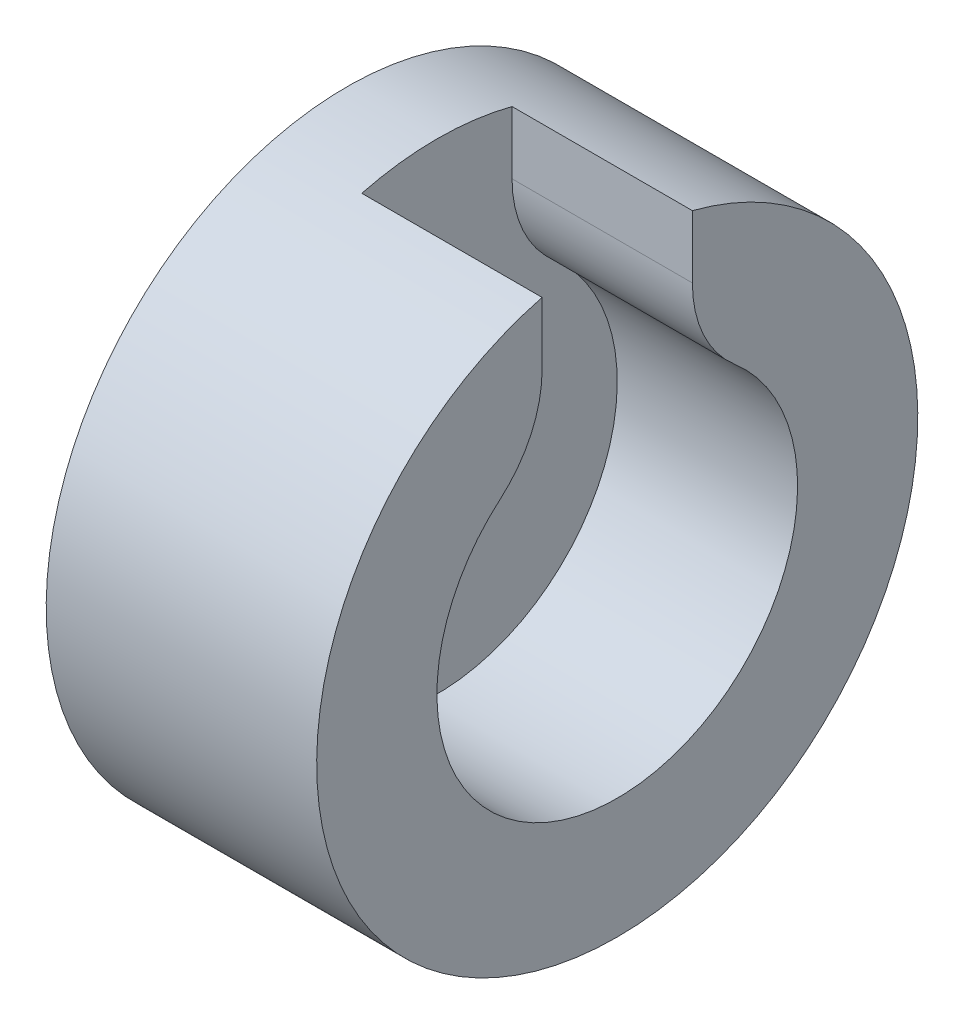
SolidWorks part; units mm, degrees
ref_plane "Front Plane" through (0, 0, 0) normal (0, 0, 1) x (1, 0, 0)
ref_plane "Top Plane" through (0, 0, 0) normal (0, 1, 0) x (1, 0, 0)
ref_plane "Right Plane" through (0, 0, 0) normal (1, 0, 0) x (0, 0, -1)
sketch "Sketch1" plane through (0, 0, 0) normal (1, 0, 0) x (0, 0, -1)
  circle A0 centre (0, 0) radius 5
  dimension "D1" = 10
extrude "Boss-Extrude1" add sketch "Sketch1" along normal blind 1.5
sketch "Sketch2" plane through (1.5, 0, 0) normal (1, 0, 0) x (0, 0, -1)
  circle A0 centre (0, 0) radius 3
  circle A1 centre (0, 0) radius 5
  dimension "D1" = 6
  dimension "D2" = 10
extrude "Boss-Extrude2" add sketch "Sketch2" along normal blind 3
sketch "Sketch3" plane through (1.5, 0, 0) normal (1, 0, 0) x (0, 0, -1)
  line L0 (-1.25, 0) -> (1.25, 0)
  line L1 (-1.25, -6) -> (1.25, -6)
  line L2 (-1.25, -6) -> (-1.25, 6)
  line L3 (-1.25, 6) -> (1.25, 6)
  line L4 (1.25, -6) -> (1.25, 6)
  line L5 (-1.25, -6) -> (1.25, 6) construction
  line L6 (-1.25, 6) -> (1.25, -6) construction
  point P0 (0, 0)
  circle M2 centre (0, 0) radius 3
  dimension "D1" = 2.5
  dimension "D2" = 2.5
  dimension "D3" = 12
extrude "Cut-Extrude1" cut sketch "Sketch3" along normal through all contours L4 L3 L2 M2 | L0 L4 L2 M2
fillet "Fillet1" radius 2 2 edges at (3, 2.7272, -1.25) (3, 2.7272, 1.25)
